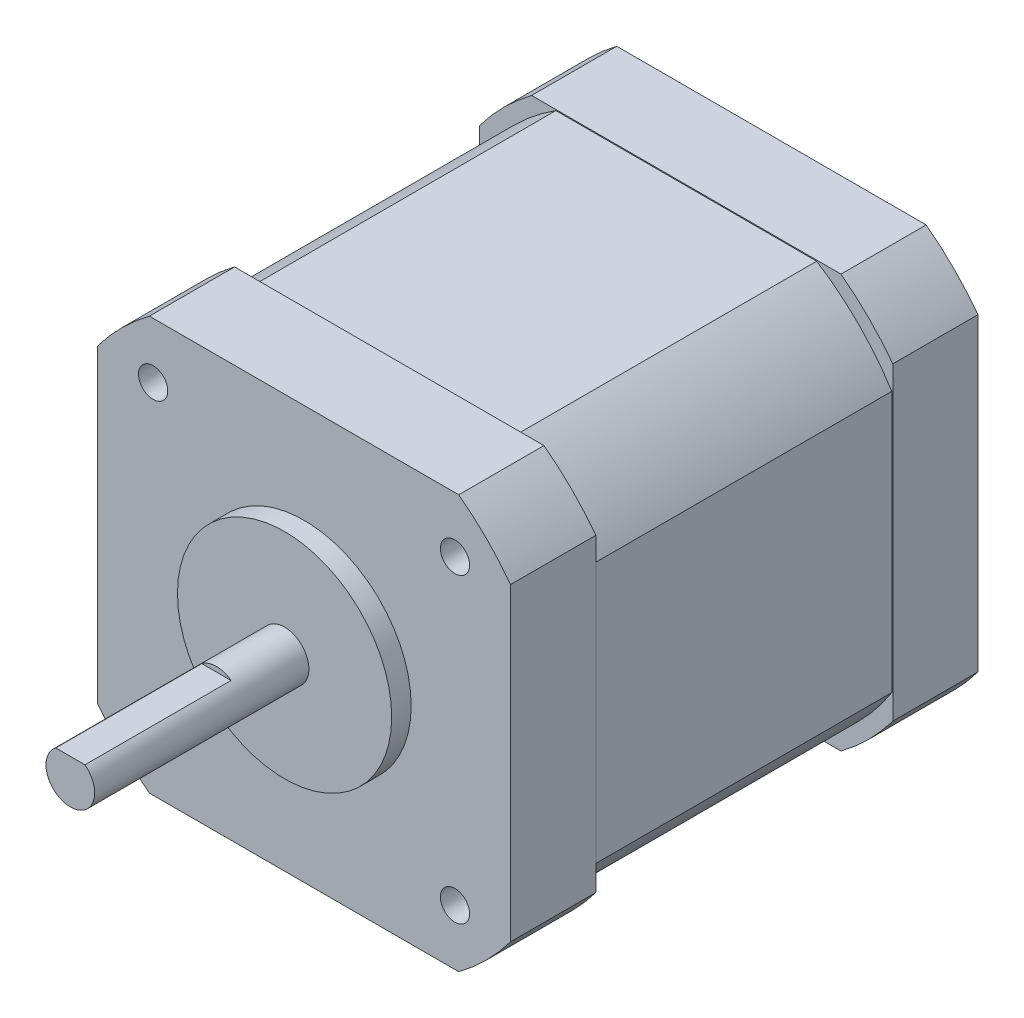
SolidWorks part; units mm, degrees
material "Plain Carbon Steel"
ref_plane "Front" through (0, 0, 0) normal (0, 0, 1) x (1, 0, 0)
ref_plane "Top" through (0, 0, 0) normal (0, 1, 0) x (1, 0, 0)
ref_plane "Right" through (0, 0, 0) normal (1, 0, 0) x (0, 0, -1)
sketch "Sketch1" plane through (0, 0, 0) normal (0, 0, 1) x (1, 0, 0)
  circle A0 centre (0, 0) radius 2.5
  dimension "D1" = 5
extrude "Boss-Extrude1" add sketch "Sketch1" along normal blind 24
sketch "Sketch2" plane through (0, 0, 0) normal (0, 0, -1) x (-1, 0, 0)
  circle A0 centre (0, 0) radius 11
  dimension "D1" = 22
extrude "Boss-Extrude2" add sketch "Sketch2" against normal blind 2
sketch "Sketch3" plane through (0, 0, 0) normal (0, 0, -1) x (-1, 0, 0)
  line L1 (21.209, -21.209) -> (-21.209, -21.209)
  line L2 (21.209, -21.209) -> (21.209, 21.209)
  line L3 (21.209, 21.209) -> (-21.209, 21.209)
  line L4 (-21.209, -21.209) -> (-21.209, 21.209)
  line L5 (21.209, -21.209) -> (-21.209, 21.209) construction
  line L6 (21.209, 21.209) -> (-21.209, -21.209) construction
  point P0 (0, 0)
  dimension "D1" = 42.418
extrude "Boss-Extrude3" add sketch "Sketch3" along normal blind 48
sketch "Sketch4" plane through (0, 0, -48) normal (0, 0, -1) x (-1, 0, 0)
  line L0 (-21.209, -15.888) -> (-21.209, -21.209)
  line L1 (15.888, -21.209) -> (21.209, -21.209)
  line L2 (21.209, 15.888) -> (21.209, 21.209)
  line L3 (-15.888, 21.209) -> (-21.209, 21.209)
  line L4 (-21.209, 21.209) -> (-21.209, -21.209)
  line L5 (-21.209, -21.209) -> (21.209, -21.209)
  line L6 (21.209, -21.209) -> (21.209, 21.209)
  line L7 (21.209, 21.209) -> (-21.209, 21.209)
  line L8 (-21.209, 21.209) -> (-21.209, 15.888)
  line L9 (-21.209, -21.209) -> (-15.888, -21.209)
  line L10 (21.209, -21.209) -> (21.209, -15.888)
  line L11 (21.209, 21.209) -> (15.888, 21.209)
  arc A0 (-21.209, -15.888) -> (-15.888, -21.209) centre (0, 0) ccw
  arc A1 (15.888, -21.209) -> (21.209, -15.888) centre (0, 0) ccw
  arc A2 (21.209, 15.888) -> (15.888, 21.209) centre (0, 0) ccw
  arc A3 (-15.888, 21.209) -> (-21.209, 15.888) centre (0, 0) ccw
  dimension "D2" = 26.5
  dimension "D1" = 0
extrude "Cut-Extrude1" cut sketch "Sketch4" against normal through all
hole_wizard "M3x0.5 螺纹孔1" positions "Sketch6" profile "Sketch5" tap size "M3x0.5" standard "ANSI Metric"
sketch "Sketch6" plane through (0, 0, 0) normal (0, 0, 1) x (1, 0, 0)
  line L0 (-16.1632, 0) -> (0, 0) construction
  line L1 (0, 0) -> (0, 15.0764) construction
  point P0 (-15.5, 15.5)
  point P11 (-15.5, -15.5)
  point P12 (15.5, -15.5)
  point P13 (15.5, 15.5)
  dimension "D1" = 31
  dimension "D2" = 31
sketch "Sketch5" plane through (-15.5, 15.5, 0) normal (1, 0, 0) x (0, -1, 0)
  line L0 (0, 0) -> (0, 8.2511)
  line L1 (0, 8.2511) -> (1.25, 7.5)
  line L2 (1.25, 7.5) -> (1.25, 6)
  line L3 (1.25, 6) -> (1.5, 6)
  line L4 (1.5, 6) -> (1.5, 0)
  line L5 (1.5, 0) -> (0, 0)
  line L10 (0, 8.2511) -> (-1.25, 7.5) construction
  line L11 (0, -6.35) -> (0, 107.95) construction
  dimension "Tap Drill Dia." = 2.5
  dimension "Tap Drill Depth" = 7.5
  dimension "Thread Major Dia." = 3
  dimension "Thread Depth" = 6
  dimension "Drill Angle" = 118
sketch "Sketch7" plane through (0, 0, 24) normal (0, 0, 1) x (1, 0, 0)
  line L0 (-1.5, 2) -> (1.5, 2)
  circle A0 centre (0, 0) radius 2.5 construction
  circle A1 centre (0, 0) radius 2.5 construction
  arc A2 (1.5, 2) -> (-1.5, 2) centre (0, 0) ccw
  dimension "D1" = 4.5
extrude "Cut-Extrude2" cut sketch "Sketch7" against normal blind 15
ref_plane "Plane1" through (0, 0, -24) normal (0, 0, 1) x (1, 0, 0)
sketch "Sketch8" plane through (0, 0, -24) normal (0, 0, 1) x (1, 0, 0)
  line L0 (-13.3944, 21.109) -> (13.3944, 21.109)
  line L1 (-5.7152, 0) -> (0, 0) construction
  line L2 (0, 0) -> (0, 8.4579) construction
  line L3 (-15.888, 21.209) -> (15.888, 21.209) construction
  line L4 (-13.3944, -21.109) -> (13.3944, -21.109)
  line L5 (-21.109, 13.3944) -> (-21.109, -13.3944)
  line L6 (-21.209, -15.888) -> (-21.209, 15.888) construction
  line L7 (21.109, 13.3944) -> (21.109, -13.3944)
  line L12 (15.888, 21.209) -> (-15.888, 21.209)
  line L13 (-21.209, 15.888) -> (-21.209, -15.888)
  line L14 (-15.888, -21.209) -> (15.888, -21.209)
  line L15 (21.209, -15.888) -> (21.209, 15.888)
  line L16 (15.888, 21.209) -> (-15.888, 21.209)
  line L17 (-21.209, 15.888) -> (-21.209, -15.888)
  line L18 (-15.888, -21.209) -> (15.888, -21.209)
  line L19 (21.209, -15.888) -> (21.209, 15.888)
  arc A0 (-13.3944, 21.109) -> (-21.109, 13.3944) centre (0, 0) ccw
  arc A1 (-21.109, -13.3944) -> (-13.3944, -21.109) centre (0, 0) ccw
  arc A2 (21.109, 13.3944) -> (13.3944, 21.109) centre (0, 0) ccw
  arc A3 (13.3944, -21.109) -> (21.109, -13.3944) centre (0, 0) ccw
  arc A5 (-15.888, 21.209) -> (-21.209, 15.888) centre (0, 0) ccw
  arc A6 (-21.209, -15.888) -> (-15.888, -21.209) centre (0, 0) ccw
  arc A7 (15.888, -21.209) -> (21.209, -15.888) centre (0, 0) ccw
  arc A8 (21.209, 15.888) -> (15.888, 21.209) centre (0, 0) ccw
  arc A9 (-15.888, 21.209) -> (-21.209, 15.888) centre (0, 0) ccw
  arc A10 (-21.209, -15.888) -> (-15.888, -21.209) centre (0, 0) ccw
  arc A11 (15.888, -21.209) -> (21.209, -15.888) centre (0, 0) ccw
  arc A12 (21.209, 15.888) -> (15.888, 21.209) centre (0, 0) ccw
  dimension "D1" = 50
  dimension "D2" = 0.1
  dimension "D3" = 0.1
  dimension "D4" = 0
extrude "Cut-Extrude3" cut sketch "Sketch8" against normal mid plane 30.5
